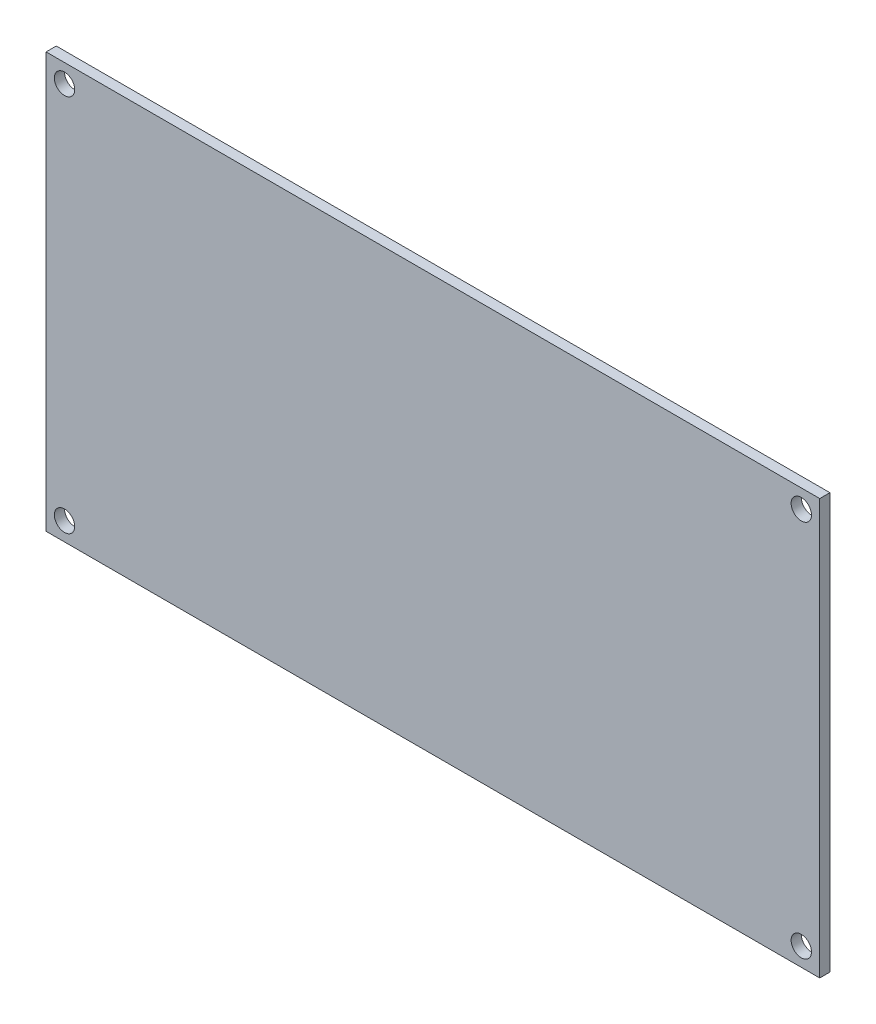
SolidWorks part; units mm, degrees
ref_plane "Plan de face" through (0, 0, 0) normal (0, 0, 1) x (1, 0, 0)
ref_plane "Plan de dessus" through (0, 0, 0) normal (0, 1, 0) x (1, 0, 0)
ref_plane "Plan de droite" through (0, 0, 0) normal (1, 0, 0) x (0, 0, -1)
sketch "Esquisse1" plane through (0, 0, 0) normal (0, 0, 1) x (1, 0, 0)
  line L1 (-119.8323, 39.9055) -> (32.1075, 39.9055)
  line L2 (-119.8323, 39.9055) -> (-119.8323, -41.6387)
  line L3 (-119.8323, -41.6387) -> (32.1075, -41.6387)
  line L4 (32.1075, 39.9055) -> (32.1075, -41.6387)
  circle A0 centre (-116.211, 36.2842) radius 2
  circle A1 centre (-116.211, -38.0174) radius 2
  circle A2 centre (28.4862, -38.0174) radius 2
  circle A3 centre (28.4862, 36.2842) radius 2
extrude "Boss.-Extru.1" add sketch "Esquisse1" along normal blind 2
